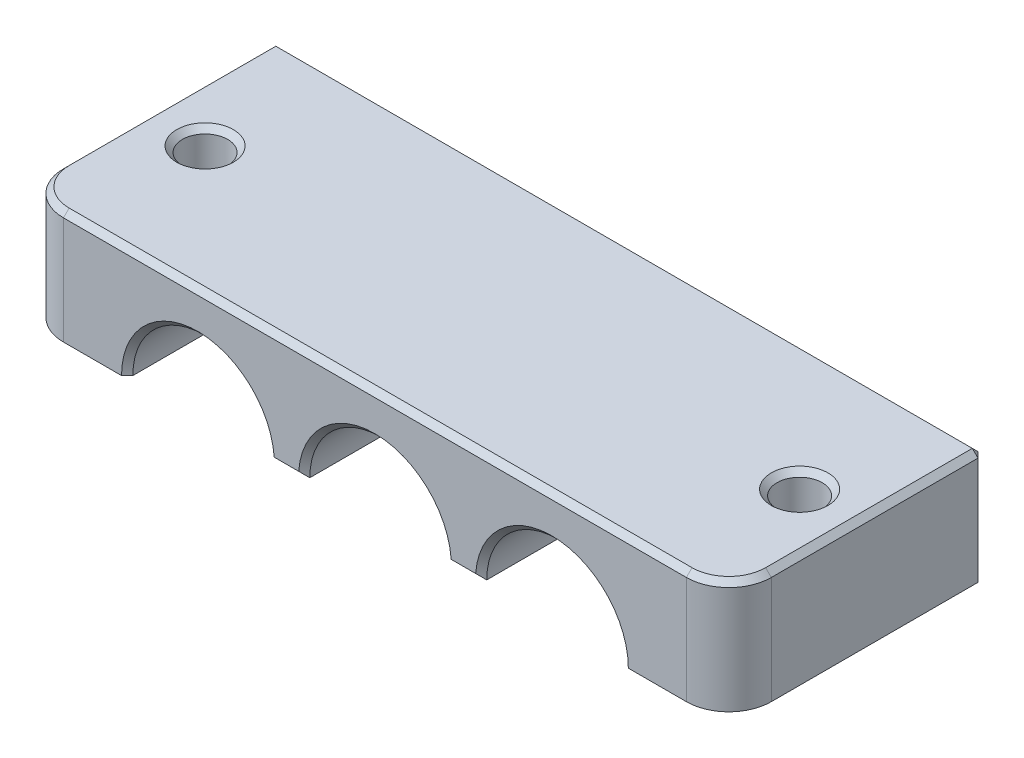
SolidWorks part; units mm, degrees
ref_plane "Front Plane" through (0, 0, 0) normal (0, 0, 1) x (1, 0, 0)
ref_plane "Top Plane" through (0, 0, 0) normal (0, 1, 0) x (1, 0, 0)
ref_plane "Right Plane" through (0, 0, 0) normal (1, 0, 0) x (0, 0, -1)
sketch "Sketch1" plane through (0, 0, 0) normal (0, 0, 1) x (1, 0, 0)
  line L0 (-7.5, 0) -> (-5, 0) construction
  line L1 (-7.5, 0) -> (-5, 0)
  line L2 (-25, 8) -> (25, 8)
  line L3 (-25, 8) -> (-25, 0)
  line L4 (-25, 0) -> (-17.5, 0)
  line L5 (25, 8) -> (25, 0)
  line L6 (5, 0) -> (7.5, 0)
  line L7 (17.5, 0) -> (25, 0)
  line L8 (0, 0) -> (0, 8) construction
  circle A0 centre (-12.5, 0) radius 5 construction
  circle A1 centre (0, 0) radius 5 construction
  circle A2 centre (12.5, 0) radius 5 construction
  arc A3 (-17.5, 0) -> (-7.5, 0) centre (-12.5, 0) cw
  arc A6 (-5, 0) -> (5, 0) centre (0, 0) cw
  arc A7 (7.5, 0) -> (17.5, 0) centre (12.5, 0) cw
  dimension "D1" = 10
  dimension "D2" = 25
  dimension "D3" = 50
  dimension "D4" = 8
extrude "Boss-Extrude1" add sketch "Sketch1" along normal blind 18
sketch "Sketch2" plane through (0, 8, 0) normal (0, 1, 0) x (1, 0, 0)
  line L0 (-21, -9) -> (21, -9) construction
  line L1 (0, 0) -> (0, -9) construction
  line L2 (25, 0) -> (-25, 0) construction
  line L3 (0, -9) -> (0, -18) construction
  line L4 (25, -18) -> (-25, -18) construction
  circle A0 centre (-21, -9) radius 1.6
  circle A1 centre (21, -9) radius 1.6
  dimension "D2" = 3.2
  dimension "D1" = 42
extrude "Cut-Extrude1" cut sketch "Sketch2" against normal through all
fillet "Fillet1" radius 3 2 edges at (-25, 4, 18) (25, 4, 18)
chamfer "Chamfer1" distance 0.4 angle 45 20 edges at (21, 8, 10.6) (-21, 8, 10.6) (12.5, 5, 0) (0, 5, 0) (-12.5, 5, 0) (0, 8, 0) (-25, 4, 0) (-25, 8, 7.5) (-24.1213, 8, 17.1213) (0, 8, 18) (24.1213, 8, 17.1213) (25, 8, 7.5) (25, 4, 0) (12.5, 5, 18) (0, 5, 18) (-12.5, 5, 18) (6.25, 0, 0) (-6.25, 0, 0) (6.25, 0, 18) (-6.25, 0, 18)
